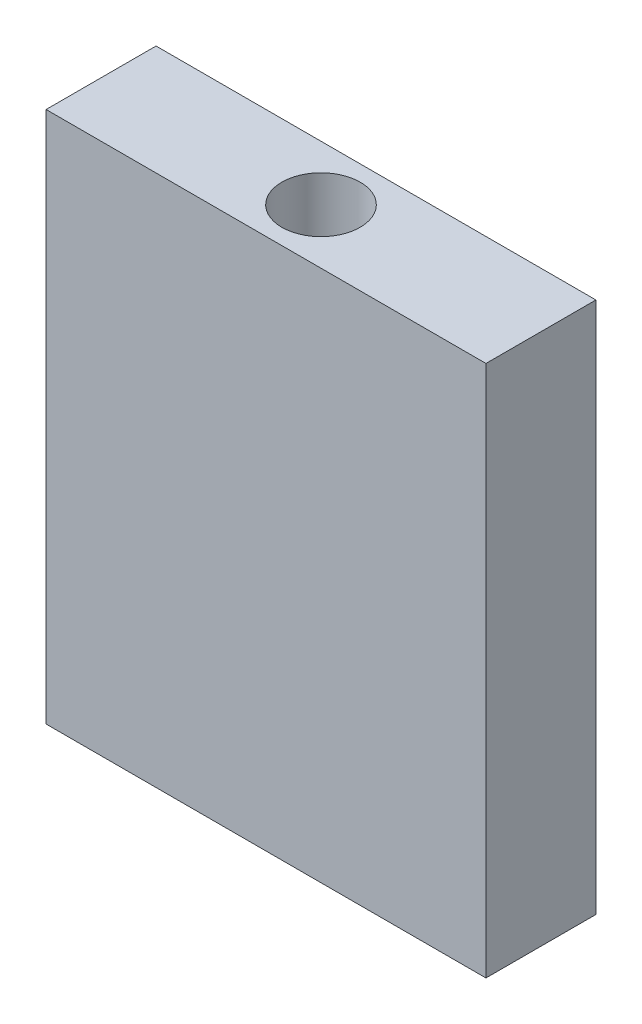
SolidWorks part; units mm, degrees
ref_plane "Front Plane" through (0, 0, 0) normal (0, 0, 1) x (1, 0, 0)
ref_plane "Top Plane" through (0, 0, 0) normal (0, 1, 0) x (1, 0, 0)
ref_plane "Right Plane" through (0, 0, 0) normal (1, 0, 0) x (0, 0, -1)
sketch "Sketch1" plane through (0, 0, 0) normal (0, 0, 1) x (1, 0, 0)
  line L1 (0, 0) -> (50, 0)
  line L2 (0, 0) -> (0, 60.5)
  line L3 (0, 60.5) -> (50, 60.5)
  line L4 (50, 0) -> (50, 60.5)
  dimension "D1" = 50
  dimension "D2" = 60.5
extrude "Boss-Extrude1" add sketch "Sketch1" along normal blind 12.5
sketch "Sketch2" plane through (0, 60.5, 0) normal (0, 1, 0) x (1, 0, 0)
  line L0 (25, 0) -> (25, -12.5) construction
  line L1 (50, 0) -> (0, 0) construction
  line L2 (50, -12.5) -> (0, -12.5) construction
  circle A0 centre (25, -6.25) radius 4.45
  dimension "D1" = 8.9
extrude "Cut-Extrude1" cut sketch "Sketch2" against normal blind 12.5
